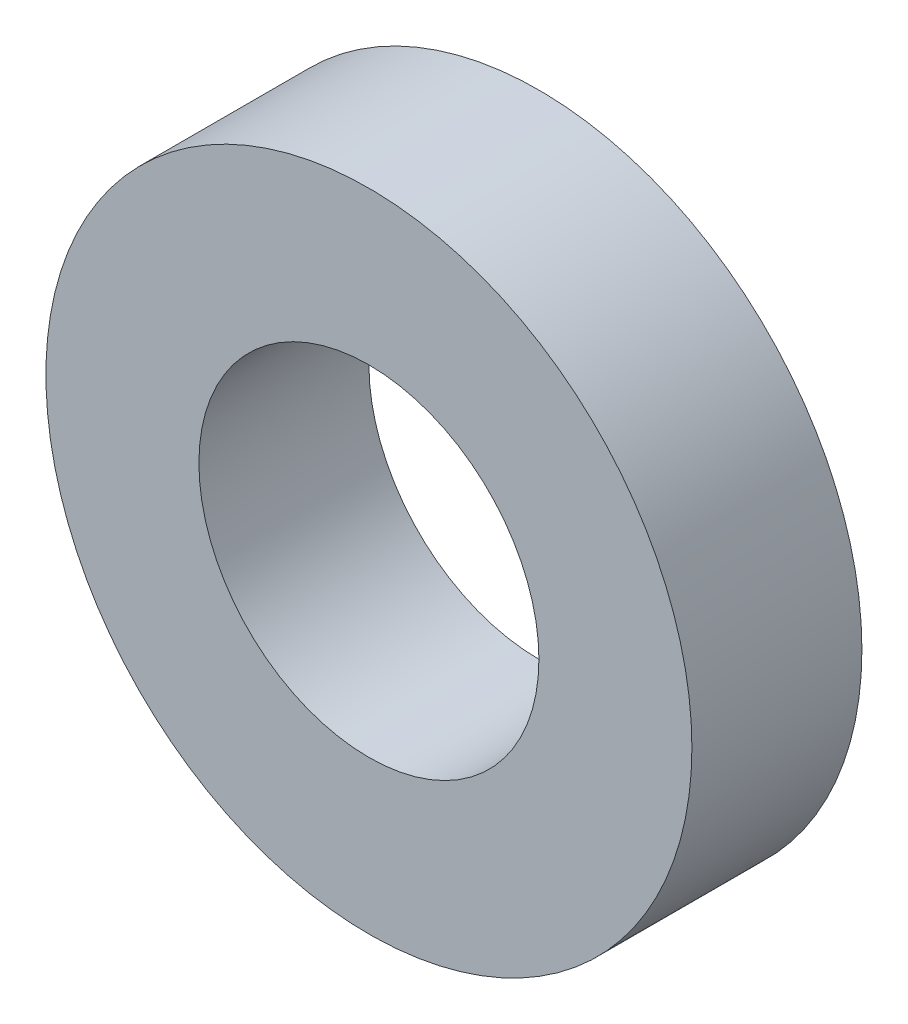
SolidWorks part; units mm, degrees
ref_plane "Front Plane" through (0, 0, 0) normal (0, 0, 1) x (1, 0, 0)
ref_plane "Top Plane" through (0, 0, 0) normal (0, 1, 0) x (1, 0, 0)
ref_plane "Right Plane" through (0, 0, 0) normal (1, 0, 0) x (0, 0, -1)
sketch "Sketch1" plane through (0, 0, 0) normal (0, 0, 1) x (1, 0, 0)
  circle A0 centre (0, 0) radius 5
  circle A1 centre (0, 0) radius 9.5
extrude "Boss-Extrude1" add sketch "Sketch1" along normal blind 5
